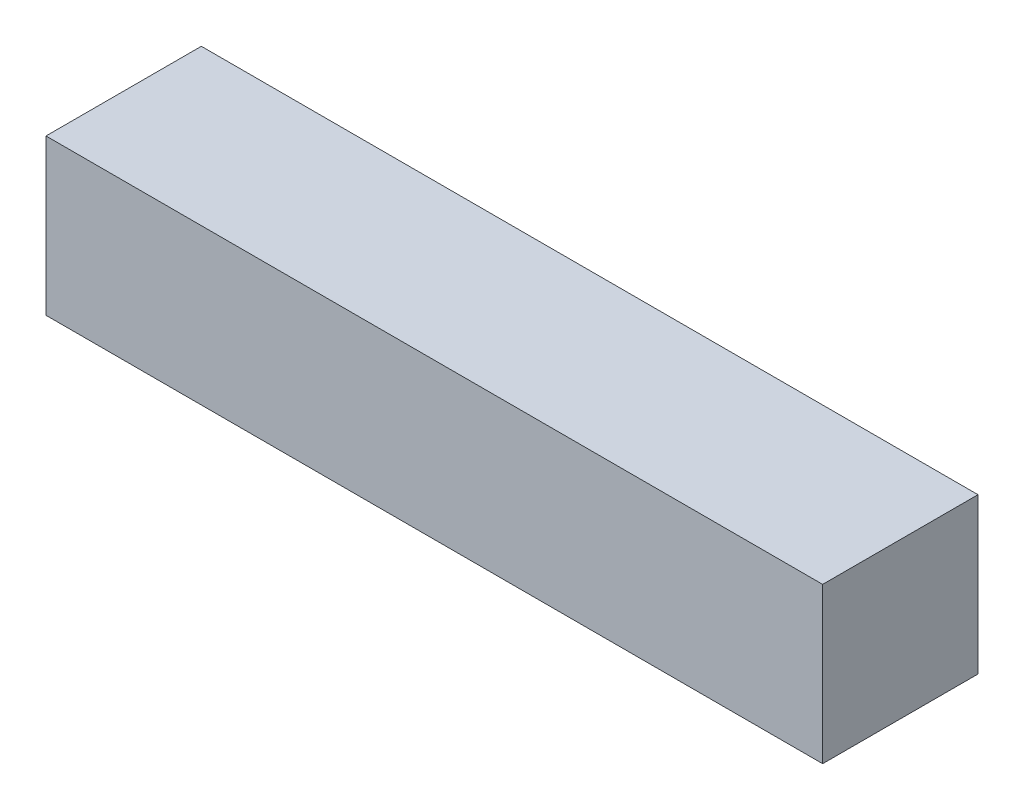
SolidWorks part; units mm, degrees
ref_plane "Front Plane" through (0, 0, 0) normal (0, 0, 1) x (1, 0, 0)
ref_plane "Top Plane" through (0, 0, 0) normal (0, 1, 0) x (1, 0, 0)
ref_plane "Right Plane" through (0, 0, 0) normal (1, 0, 0) x (0, 0, -1)
sketch "Sketch1" plane through (0, 0, 0) normal (0, 0, 1) x (1, 0, 0)
  line L1 (0, 0) -> (110, 0)
  line L2 (0, 0) -> (0, 22)
  line L3 (0, 22) -> (110, 22)
  line L4 (110, 0) -> (110, 22)
  dimension "D1" = 110
  dimension "D2" = 22
extrude "Boss-Extrude1" add sketch "Sketch1" along normal blind 22
